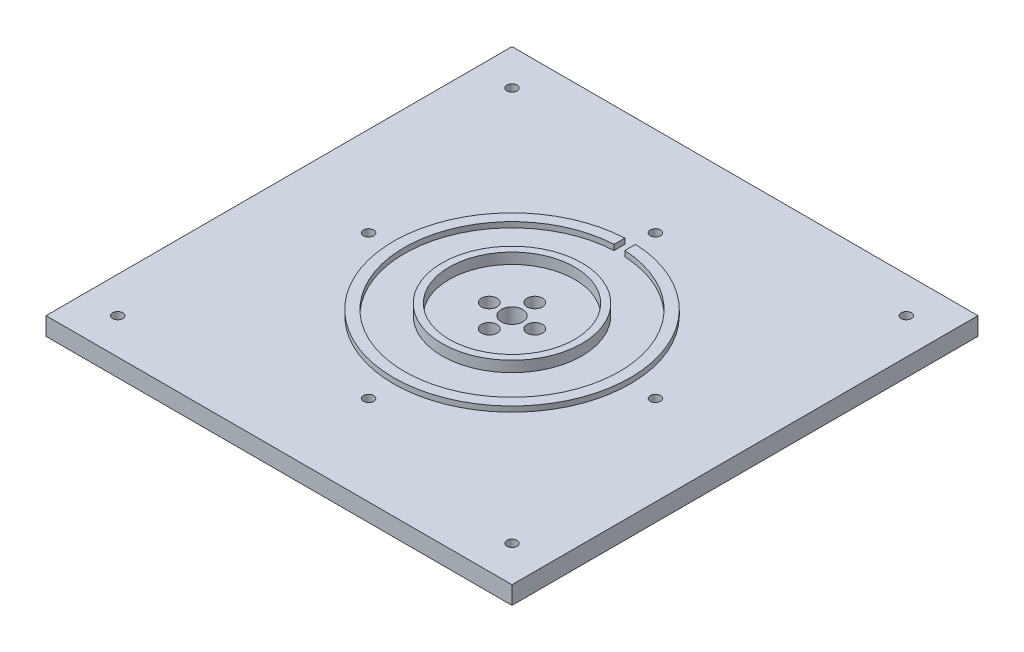
SolidWorks part; units mm, degrees
ref_plane "Front Plane" through (0, 0, 0) normal (0, 0, 1) x (1, 0, 0)
ref_plane "Top Plane" through (0, 0, 0) normal (0, 1, 0) x (1, 0, 0)
ref_plane "Right Plane" through (0, 0, 0) normal (1, 0, 0) x (0, 0, -1)
sketch "Sketch1" plane through (0, 0, 0) normal (0, 1, 0) x (1, 0, 0)
  line L1 (-65, -65) -> (65, -65)
  line L2 (-65, -65) -> (-65, 65)
  line L3 (-65, 65) -> (65, 65)
  line L4 (65, -65) -> (65, 65)
  line L5 (-65, -65) -> (65, 65) construction
  line L6 (-65, 65) -> (65, -65) construction
  circle A0 centre (0, 0) radius 26
  circle A1 centre (0, 0) radius 31
  circle A2 centre (0, 0) radius 24
  dimension "D1" = 52
  dimension "D2" = 62
  dimension "D3" = 48
  dimension "D4" = 130
  dimension "D5" = 130
extrude "Boss-Extrude2" add sketch "Sketch1" along normal blind 5 contours L1 L4 L3 L2 A1 | A1 A0 | A0 A2 | A2
sketch "Sketch2" plane through (0, 5, 0) normal (0, 1, 0) x (1, 0, 0)
  circle A0 centre (0, 0) radius 30
  circle A1 centre (0, 0) radius 33
  dimension "D1" = 60
  dimension "D2" = 66
extrude "Boss-Extrude3" add sketch "Sketch2" along normal blind 1.5
sketch "Sketch3" plane through (0, 5, 0) normal (0, 1, 0) x (1, 0, 0)
  circle A0 centre (0, 6.35) radius 2.15
  circle A1 centre (6.35, 0) radius 2.15
  circle A2 centre (0, -6.35) radius 2.15
  circle A3 centre (-6.35, 0) radius 2.15
  circle A4 centre (6.35, 0) radius 2.15
  circle A5 centre (0, -6.35) radius 2.15
  circle A6 centre (-6.35, 0) radius 2.15
  circle A7 centre (0, 0) radius 3
  point P12 (0, 0)
  point P19 (0, 0)
  dimension "D1" = 4.3
  dimension "D5" = 6
  dimension "D2" = 6.35
  dimension "D3" = 4
  dimension "D4" = 4
extrude "Cut-Extrude1" cut sketch "Sketch3" against normal blind 5 contours A0 | A1 | A2 | A3 | A7
sketch "Sketch4" plane through (0, 0, 0) normal (0, -1, 0) x (-1, 0, 0)
  circle A0 centre (-6.35, 0) radius 3
  circle A1 centre (0, 6.35) radius 3
  circle A2 centre (6.35, 0) radius 3
  circle A3 centre (0, -6.35) radius 3
  point P12 (0, 0)
  dimension "D1" = 6
  dimension "D2" = 4
extrude "Cut-Extrude2" [suppressed] cut sketch "Sketch4" against normal blind 3
sketch "Sketch5" plane through (0, 5, 0) normal (0, 1, 0) x (1, 0, 0)
  line L0 (-65, 65) -> (65, 65) construction
  line L1 (-65, -65) -> (-65, 65) construction
  line L2 (-78.7821, 0) -> (65.875, 0) construction
  line L3 (0, 66.4229) -> (0, -72.9983) construction
  circle A0 centre (-55, 55) radius 1.42
  circle A1 centre (-55, -55) radius 1.42
  circle A2 centre (55, -55) radius 1.42
  circle A3 centre (55, 55) radius 1.42
  circle A4 centre (0, 40) radius 1.42
  circle A5 centre (-40, 0) radius 1.42
  circle A6 centre (40, 0) radius 1.42
  circle A7 centre (0, -40) radius 1.42
  point P28 (0, 0)
  dimension "D1" = 2.84
  dimension "D4" = 40
  dimension "D5" = 2.84
  dimension "D2" = 10
  dimension "D3" = 10
  dimension "D6" = 4
extrude "Cut-Extrude3" cut sketch "Sketch5" against normal blind 10
sketch "Sketch6" plane through (0, 5, 0) normal (0, 1, 0) x (1, 0, 0)
  circle A0 centre (0, 0) radius 19.5
  circle A1 centre (0, 0) radius 17.5
  dimension "D1" = 39
  dimension "D2" = 35
extrude "Boss-Extrude4" add sketch "Sketch6" along normal blind 3
sketch "Sketch7" plane through (0, 6.5, 0) normal (0, 1, 0) x (1, 0, 0)
  line L1 (-1.5, 27.4955) -> (1.5, 27.4955)
  line L2 (-1.5, 27.4955) -> (-1.5, 35.3153)
  line L3 (-1.5, 35.3153) -> (1.5, 35.3153)
  line L4 (1.5, 27.4955) -> (1.5, 35.3153)
  line L5 (-1.5, 27.4955) -> (1.5, 35.3153) construction
  line L6 (-1.5, 35.3153) -> (1.5, 27.4955) construction
  point P0 (0, 31.4054)
  dimension "D1" = 3
  dimension "D2" = 0
extrude "Cut-Extrude5" cut sketch "Sketch7" along direction (0, 1, 0) on the side against the normal up to surface (1.5 mm away)
